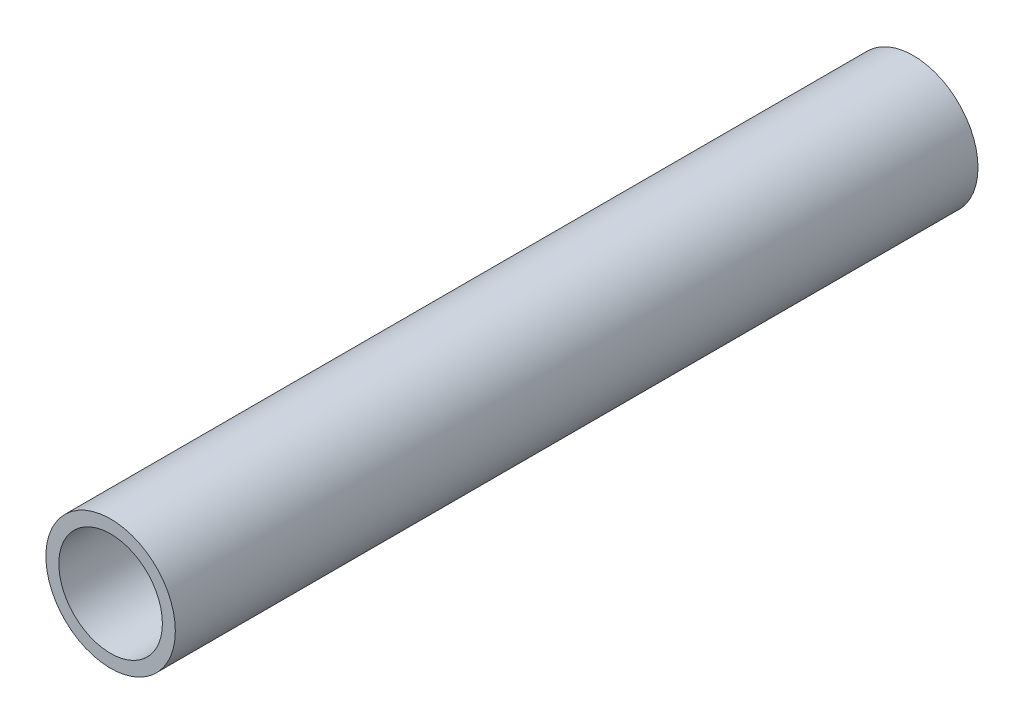
SolidWorks part; units mm, degrees
ref_plane "Front Plane" through (0, 0, 0) normal (0, 0, 1) x (1, 0, 0)
ref_plane "Top Plane" through (0, 0, 0) normal (0, 1, 0) x (1, 0, 0)
ref_plane "Right Plane" through (0, 0, 0) normal (1, 0, 0) x (0, 0, -1)
other "Default"
sketch "Sketch1" plane through (0, 0, 0) normal (0, 0, 1) x (1, 0, 0)
  circle A0 centre (0, 0) radius 15.875
  circle A1 centre (0, 0) radius 12.7
  dimension "ID" = 25.4
  dimension "OD" = 31.75
extrude "Boss-Extrude1" add sketch "Sketch1" along normal blind 196.85
